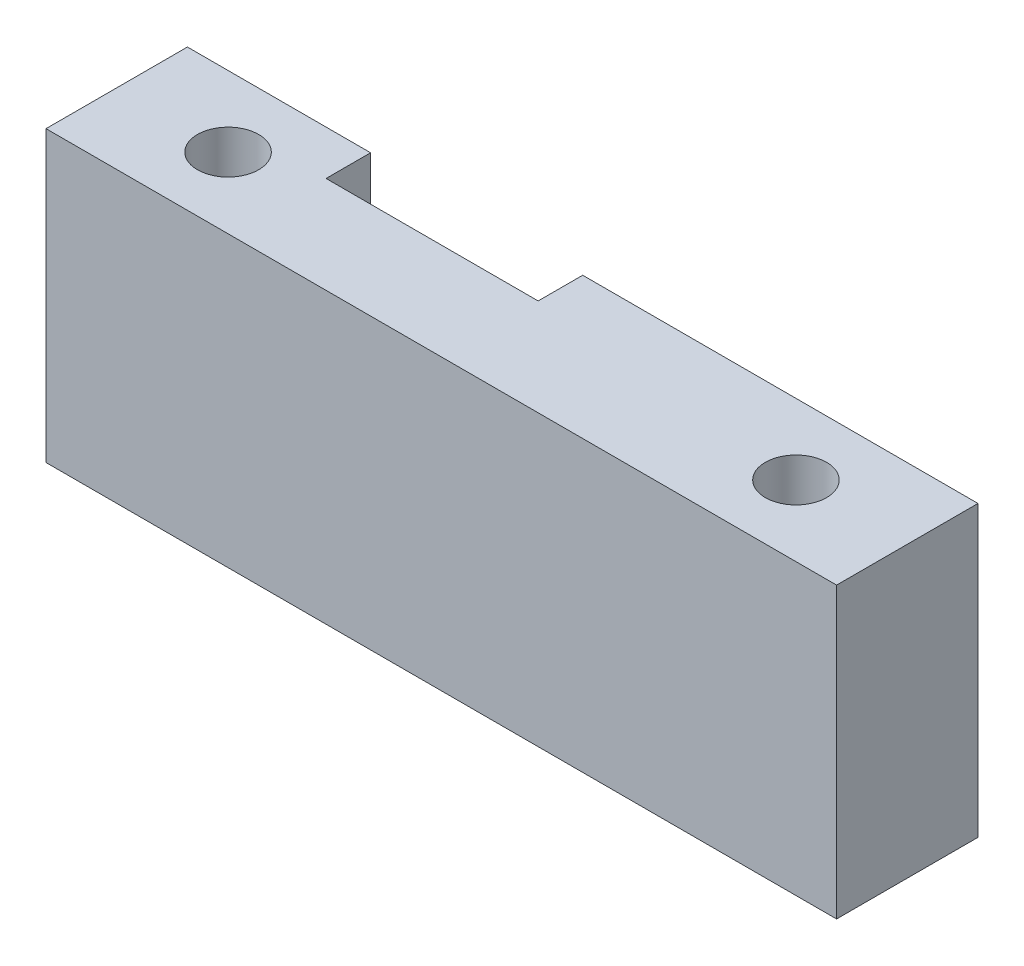
SolidWorks part; units mm, degrees
material "6061 Alloy"
ref_plane "Front Plane" through (0, 0, 0) normal (0, 0, 1) x (1, 0, 0)
ref_plane "Top Plane" through (0, 0, 0) normal (0, 1, 0) x (1, 0, 0)
ref_plane "Right Plane" through (0, 0, 0) normal (1, 0, 0) x (0, 0, -1)
sketch "Sketch1" plane through (0, 0, 0) normal (0, 1, 0) x (1, 0, 0)
  line L1 (-10, 6.35) -> (61, 6.35)
  line L2 (-10, 6.35) -> (-10, -6.35)
  line L3 (-10, -6.35) -> (61, -6.35)
  line L4 (61, 6.35) -> (61, -6.35)
  line L5 (25.5, -6.35) -> (25.5, 6.35) construction
  line L6 (-10, 0) -> (61, 0) construction
  circle A0 centre (0, 0) radius 2.75
  circle A1 centre (51, 0) radius 2.75
  point P223 (25.5, 0)
  dimension "D1" = 5.5
  dimension "D2" = 25.5
  dimension "D3" = 10
  dimension "D4" = 12.7
extrude "Boss-Extrude1" add sketch "Sketch1" along normal blind 25.97
sketch "Sketch2" plane through (0, 0, -6.35) normal (0, 0, -1) x (-1, 0, 0)
  line L0 (-61, 25.97) -> (-61, 0) construction
  line L1 (10, 0) -> (-61, 0) construction
  line L2 (10, 0) -> (10, 25.97) construction
  line L3 (10, 25.97) -> (-61, 25.97) construction
  line L4 (-61, 0) -> (-61, 25.97) construction
  line L5 (-25.5, 25.97) -> (-25.5, 0) construction
  line L6 (10, 12.985) -> (-61, 12.985) construction
  line L7 (-61, 25.97) -> (10, 25.97) construction
  line L17 (-25.5, 25.97) -> (-6.45, 25.97)
  line L18 (-43.1923, 12.985) -> (-6.45, 12.985) construction
  line L19 (-25.5, 25.97) -> (-25.5, 0)
  line L20 (-25.5, 0) -> (-6.45, 0)
  line L21 (-6.45, 25.97) -> (-6.45, 0)
  line L22 (-15.975, 0) -> (-15.975, 25.97) construction
  line L23 (-25.5, 12.985) -> (-6.45, 12.985) construction
  point P197 (-15.975, 12.985)
  dimension "D1" = 19.05
extrude "Cut-Extrude1" cut sketch "Sketch2" against normal blind 4
